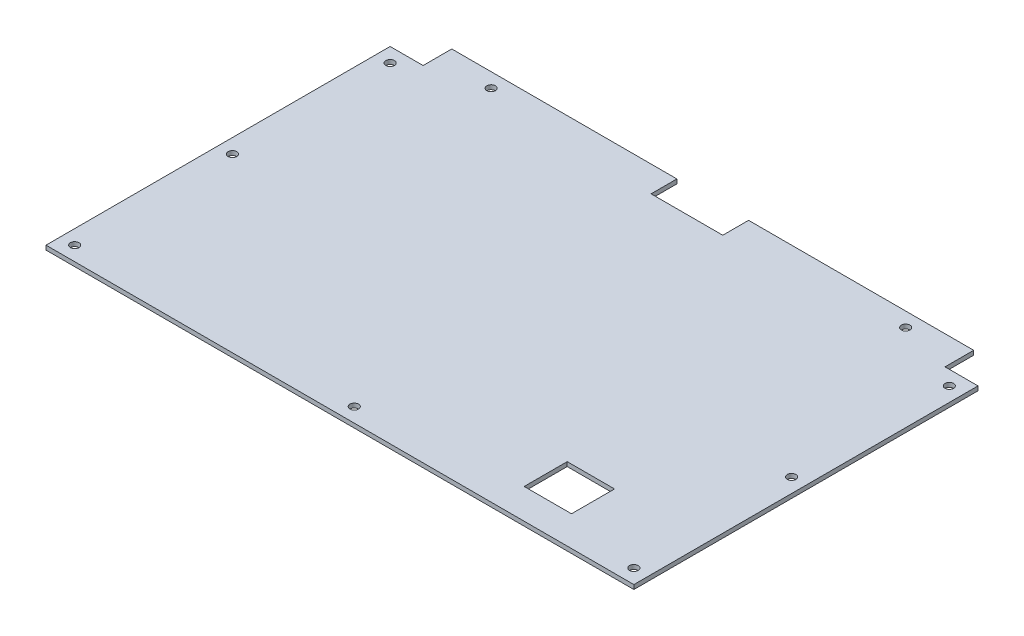
SolidWorks part; units mm, degrees
ref_plane "Alzado" through (0, 0, 0) normal (0, 0, 1) x (1, 0, 0)
ref_plane "Planta" through (0, 0, 0) normal (0, 1, 0) x (1, 0, 0)
ref_plane "Vista lateral" through (0, 0, 0) normal (1, 0, 0) x (0, 0, -1)
sketch "Croquis1" plane through (0, 0, 0) normal (0, 1, 0) x (1, 0, 0)
  line L0 (182, 120) -> (205, 120)
  line L1 (-205, 120) -> (-182, 120)
  line L2 (-205, 120) -> (-205, -120)
  line L3 (-205, -120) -> (205, -120)
  line L4 (205, 120) -> (205, -120)
  line L5 (-205, 120) -> (205, -120) construction
  line L6 (-205, -120) -> (205, 120) construction
  line L9 (-25, 122) -> (25, 122)
  line L11 (0, 0) -> (0, 42.3594) construction
  line L12 (0, 0) -> (98.6602, 0) construction
  line L13 (-182, 120) -> (-182, 140)
  line L14 (-182, 140) -> (-25, 140)
  line L15 (-25, 122) -> (-25, 140)
  line L16 (182, 120) -> (182, 140)
  line L19 (25, 140) -> (25, 122)
  line L20 (25, 140) -> (182, 140)
  circle A0 centre (-195, 110) radius 3
  circle A1 centre (-195, 0) radius 3
  circle A2 centre (-195, -110) radius 3
  circle A3 centre (195, -110) radius 3
  circle A4 centre (195, 0) radius 3
  circle A5 centre (195, 110) radius 3
  circle A6 centre (0, -110) radius 3
  circle A7 centre (144.5497, 130) radius 3
  circle A8 centre (-144.5497, 130) radius 3
  point P0 (0, 0)
  point P33 (144.5497, 130)
  dimension "D3" = 6
  dimension "D7" = 6
  dimension "D8" = 6
  dimension "D13" = 6
  dimension "D1" = 240
  dimension "D2" = 410
  dimension "D4" = 20
  dimension "D5" = 10
  dimension "D6" = 10
  dimension "D9" = 23
  dimension "D10" = 50
  dimension "D11" = 18
  dimension "D12" = 10
extrude "Saliente-Extruir1" add sketch "Croquis1" along normal blind 3
sketch "Croquis2" plane through (0, 3, 0) normal (0, 1, 0) x (1, 0, 0)
  line L0 (107.4964, -99) -> (140.4964, -99)
  line L5 (-205, -99) -> (205, -99)
  line L6 (-205, 120) -> (-205, -120) construction
  line L7 (205, -120) -> (205, 120) construction
  line L8 (-205, -120) -> (205, -120) construction
  line L9 (107.4964, -69) -> (140.4964, -69)
  line L10 (107.4964, -69) -> (107.4964, -99)
  line L12 (140.4964, -69) -> (140.4964, -99)
  point P8 (130.06, -99)
  dimension "D1" = 21
  dimension "D2" = 33
  dimension "D3" = 30
extrude "Cortar-Extruir2" cut sketch "Croquis2" against normal blind 3 contours L12 L9 L10 L0
